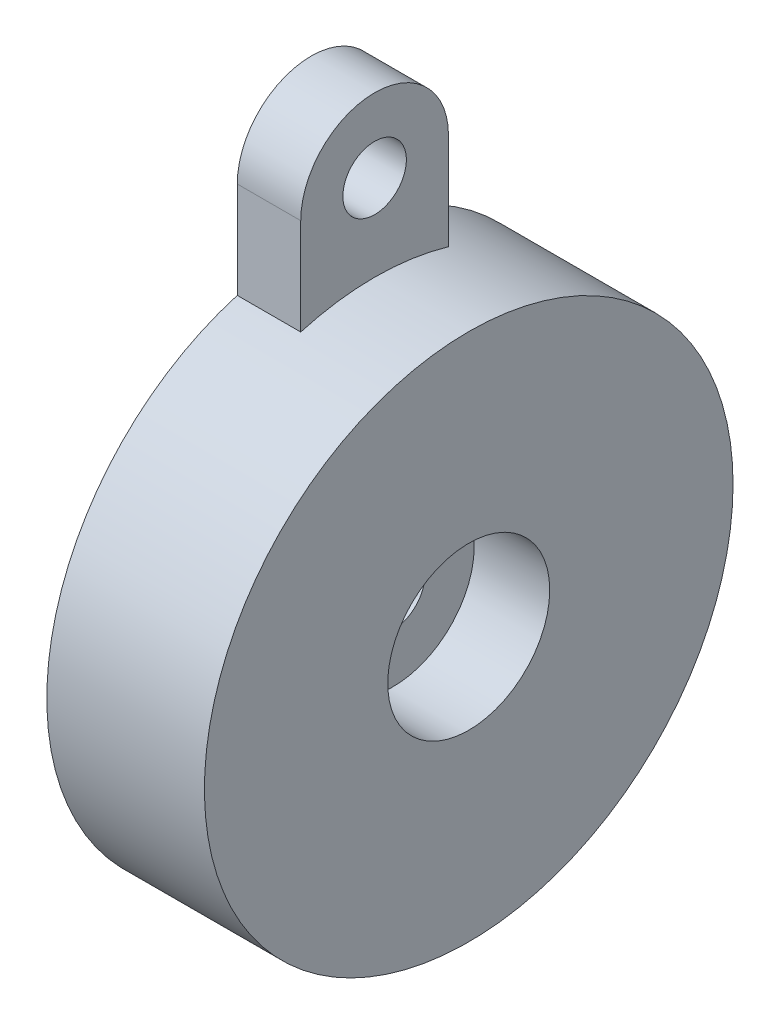
SolidWorks part; units mm, degrees
ref_plane "Front Plane" through (0, 0, 0) normal (0, 0, 1) x (1, 0, 0)
ref_plane "Top Plane" through (0, 0, 0) normal (0, 1, 0) x (1, 0, 0)
ref_plane "Right Plane" through (0, 0, 0) normal (1, 0, 0) x (0, 0, -1)
sketch "Sketch1" plane through (0, 0, 0) normal (1, 0, 0) x (0, 0, -1)
  circle A0 centre (0, 0) radius 12.075
  dimension "D1" = 24.15
extrude "Boss-Extrude1" add sketch "Sketch1" along normal mid plane 7.2
sketch "Sketch2" plane through (-3.6, 0, 0) normal (-1, 0, 0) x (0, 0, 1)
  line L0 (0, 0) -> (0, 16) construction
  line L1 (-3.375, 0) -> (-3.375, 16)
  line L2 (3.375, 0) -> (3.375, 16)
  arc A0 (-3.375, 0) -> (3.375, 0) centre (0, 0) ccw
  arc A1 (3.375, 16) -> (-3.375, 16) centre (0, 16) ccw
  point P3 (0, 8)
  dimension "D1" = 6.75
  dimension "D2" = 16
extrude "Boss-Extrude2" add sketch "Sketch2" against normal blind 2.9
sketch "Sketch3" plane through (-3.6, 0, 0) normal (-1, 0, 0) x (0, 0, 1)
  circle A0 centre (0, 0) radius 6.125
  dimension "D1" = 12.25
extrude "Boss-Extrude3" add sketch "Sketch3" along normal blind 2.25
sketch "Sketch4" plane through (-5.85, 0, 0) normal (-1, 0, 0) x (0, 0, 1)
  circle A0 centre (0, 0) radius 3.0625
  dimension "D1" = 6.125
extrude "Cut-Extrude1" cut sketch "Sketch4" against normal blind 4.44
sketch "Sketch5" plane through (-1.41, 0, 0) normal (-1, 0, 0) x (0, 0, 1)
  circle A0 centre (0, 0) radius 1.45
  dimension "D1" = 2.9
extrude "Cut-Extrude2" cut sketch "Sketch5" against normal through all
sketch "Sketch6" plane through (3.6, 0, 0) normal (1, 0, 0) x (0, 0, -1)
  circle A0 centre (0, 0) radius 3.7
extrude "Cut-Extrude3" cut sketch "Sketch6" against normal blind 3.45
sketch "Sketch7" plane through (-3.6, 0, 0) normal (-1, 0, 0) x (0, 0, 1)
  circle A0 centre (0, 16) radius 1.45
  circle A1 centre (0, 0) radius 1.45 construction
extrude "Cut-Extrude4" cut sketch "Sketch7" against normal through all
